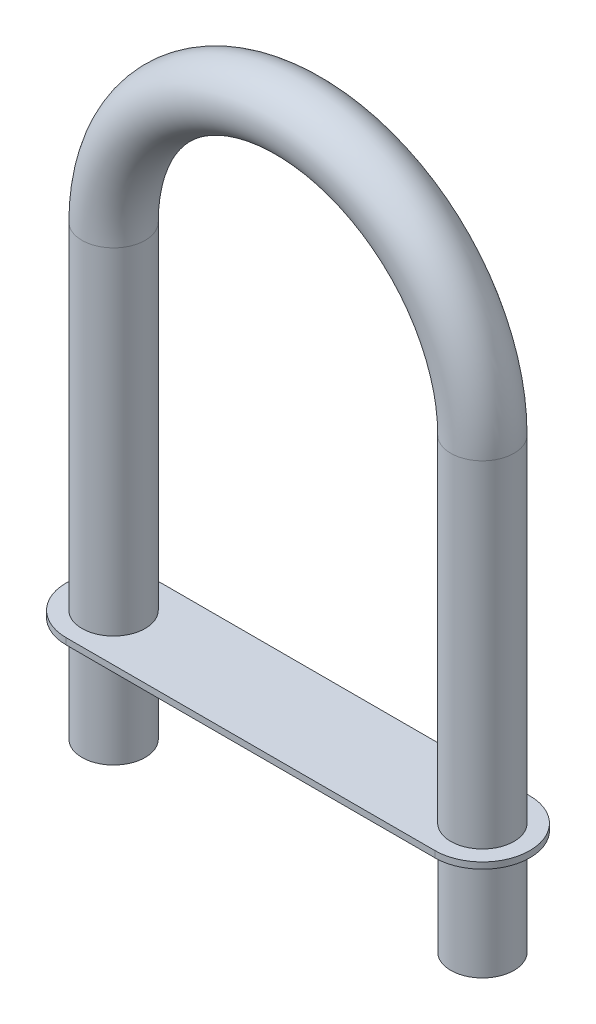
SolidWorks part; units mm, degrees
material "AISI 1020"
ref_plane "Front Plane" through (0, 0, 0) normal (0, 0, 1) x (1, 0, 0)
ref_plane "Top Plane" through (0, 0, 0) normal (0, 1, 0) x (1, 0, 0)
ref_plane "Right Plane" through (0, 0, 0) normal (1, 0, 0) x (0, 0, -1)
sketch "Sketch1" plane through (0, 0, 0) normal (0, 1, 0) x (1, 0, 0)
  line L0 (-17.5, 0) -> (0, 0) construction
  circle A0 centre (-17.5, 0) radius 3
  dimension "D1" = 6
  dimension "D2" = 17.5
sketch "Sketch2" plane through (0, 0, 0) normal (0, 0, 1) x (1, 0, 0)
  line L0 (0, 0) -> (-17.5, 0) construction
  line L2 (-17.5, 0) -> (-17.5, 42.5)
  line L6 (17.5, 42.5) -> (17.5, 0)
  line L7 (17.5, 0) -> (0, 0) construction
  arc A3 (17.5, 42.5) -> (-17.5, 42.5) centre (0, 42.5) ccw
  point P3 (0, 60)
  dimension "D1" = 17.5
  dimension "D2" = 17.5
  dimension "D3" = 60
sweep "Sweep1" add profiles "Sketch1" path "Sketch2"
cosmetic thread "Cosmetic Thread1"
cosmetic thread "Cosmetic Thread2"
ref_plane "Plane1" through (0, 10, 0) normal (0, 1, 0) x (1, 0, 0)
sketch "Sketch3" plane through (0, 10, 0) normal (0, 1, 0) x (1, 0, 0)
  line L0 (-17.5, 4.5) -> (-17.5, -4.5) construction
  line L1 (-17.5, -4.5) -> (17.5, -4.5)
  line L3 (-17.5, 4.5) -> (17.5, 4.5)
  line L5 (17.5, -4.5) -> (17.5, 4.5) construction
  arc A0 (-17.5, 4.5) -> (-17.5, -4.5) centre (-17.5, 0) ccw
  arc A1 (17.5, -4.5) -> (17.5, 4.5) centre (17.5, 0) ccw
  circle A4 centre (-17.5, 0) radius 3 construction
  circle A5 centre (-17.5, 0) radius 3 construction
  circle A6 centre (17.5, 0) radius 3 construction
  point P5 (17.1974, 0)
  dimension "D1" = 9
extrude "Boss-Extrude1" add sketch "Sketch3" along normal blind 0.6
